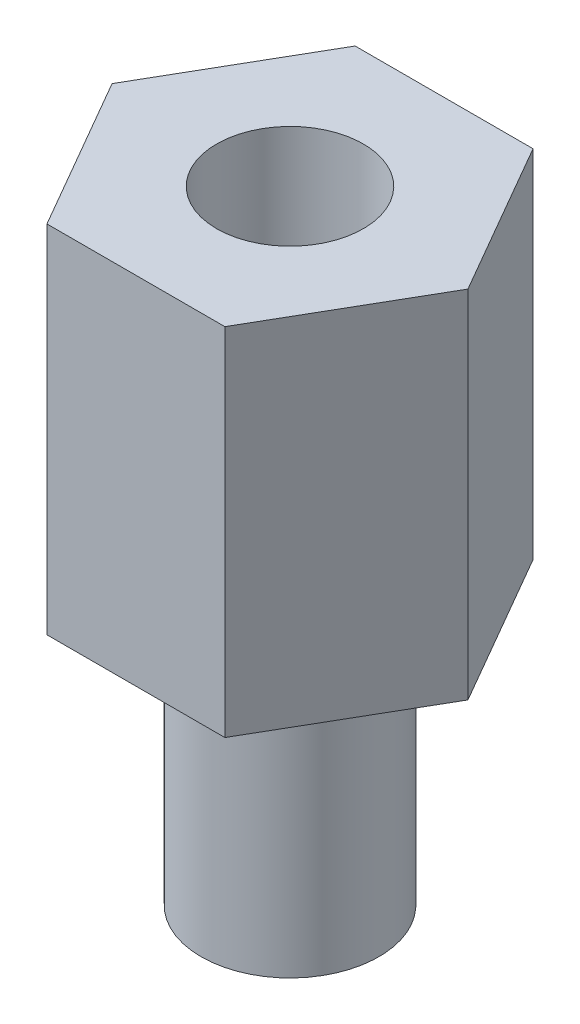
SolidWorks part; units mm, degrees
ref_plane "Front Plane" through (0, 0, 0) normal (0, 0, 1) x (1, 0, 0)
ref_plane "Top Plane" through (0, 0, 0) normal (0, 1, 0) x (1, 0, 0)
ref_plane "Right Plane" through (0, 0, 0) normal (1, 0, 0) x (0, 0, -1)
sketch "Sketch1" plane through (0, 0, 0) normal (0, 1, 0) x (1, 0, 0)
  circle A0 centre (0, 0) radius 2
extrude "Boss-Extrude1" add sketch "Sketch1" against normal blind 6
sketch "Sketch2" plane through (0, 0, 0) normal (0, 1, 0) x (1, 0, 0)
  line L1 (4, 0) -> (2, 3.4641)
  line L2 (2, 3.4641) -> (-2, 3.4641)
  line L3 (-2, 3.4641) -> (-4, 0)
  line L4 (-4, 0) -> (-2, -3.4641)
  line L5 (-2, -3.4641) -> (2, -3.4641)
  line L6 (2, -3.4641) -> (4, 0)
  circle A0 centre (0, 0) radius 4 construction
extrude "Boss-Extrude2" add sketch "Sketch2" along normal blind 8
hole_wizard "Tap Drill for M4x0.7 Tap1" positions "Sketch4" profile "Sketch3" hole size "M4x0.7" standard "ANSI Metric"
sketch "Sketch4" plane through (0, 8, 0) normal (0, 1, 0) x (1, 0, 0)
  point P0 (0, 0)
sketch "Sketch3" plane through (0, 8, 0) normal (1, 0, 0) x (0, 0, 1)
  line L0 (0, 0) -> (0, 7.9914)
  line L1 (0, 7.9914) -> (1.65, 7)
  line L2 (1.65, 7) -> (1.65, 0)
  line L5 (1.65, 0) -> (0, 0)
  line L10 (0, 7.9914) -> (-1.65, 7) construction
  line L11 (0, -6.35) -> (0, 107.95) construction
  dimension "Hole Dia." = 3.3
  dimension "Hole Depth" = 7
  dimension "Drill Angle" = 118
